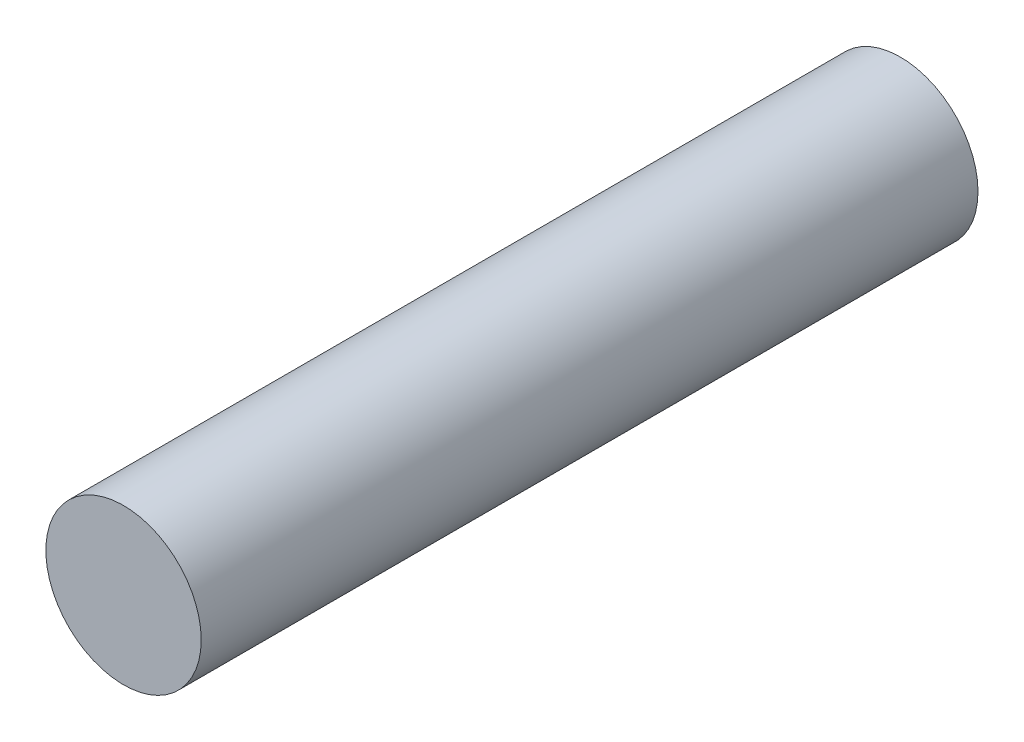
SolidWorks part; units mm, degrees
material "Stainless Steel (ferritic)"
ref_plane "Front Plane" through (0, 0, 0) normal (0, 0, 1) x (1, 0, 0)
ref_plane "Top Plane" through (0, 0, 0) normal (0, 1, 0) x (1, 0, 0)
ref_plane "Right Plane" through (0, 0, 0) normal (1, 0, 0) x (0, 0, -1)
sketch "Sketch1" plane through (0, 0, 0) normal (0, 0, 1) x (1, 0, 0)
  circle A0 centre (0, 0) radius 0.5
  dimension "D1" = 1
extrude "Boss-Extrude1" add sketch "Sketch1" along normal mid plane 5
